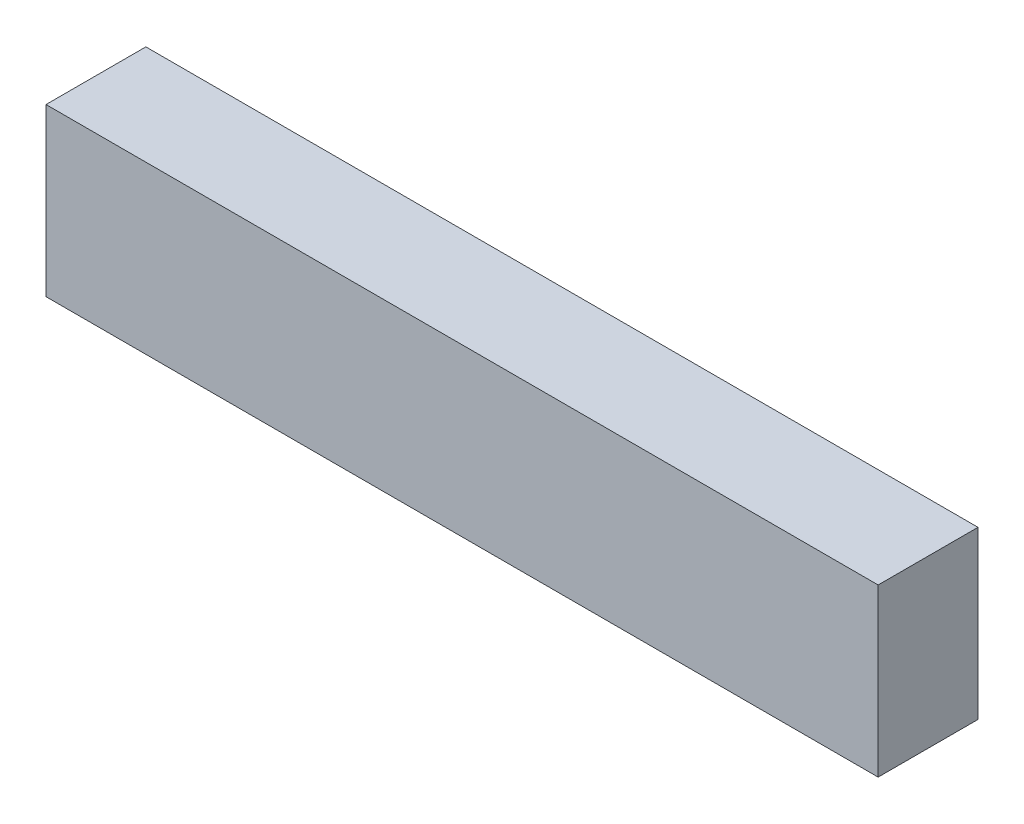
SolidWorks part; units mm, degrees
ref_plane "Front Plane" through (0, 0, 0) normal (0, 0, 1) x (1, 0, 0)
ref_plane "Top Plane" through (0, 0, 0) normal (0, 1, 0) x (1, 0, 0)
ref_plane "Right Plane" through (0, 0, 0) normal (1, 0, 0) x (0, 0, -1)
sketch "Sketch1" plane through (0, 0, 0) normal (0, 0, 1) x (1, 0, 0)
  line L1 (0, 0) -> (50, 0)
  line L2 (0, 0) -> (0, 10)
  line L3 (0, 10) -> (50, 10)
  line L4 (50, 0) -> (50, 10)
  dimension "D1" = 50
  dimension "D2" = 10
extrude "Boss-Extrude1" add sketch "Sketch1" along normal blind 6
